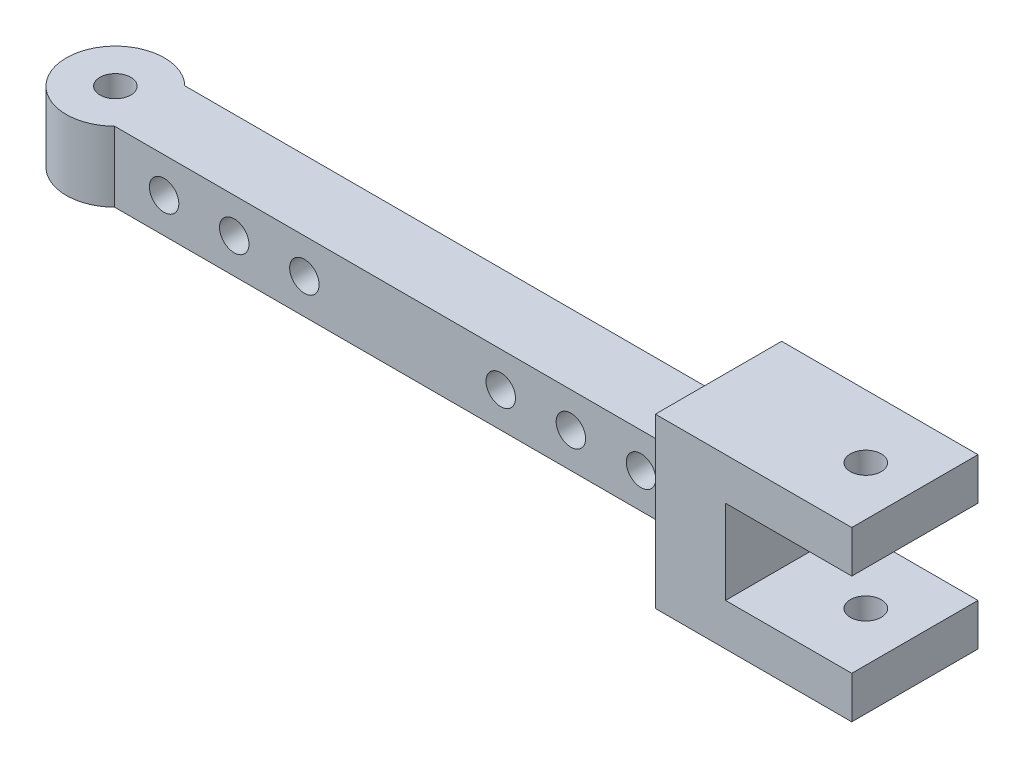
SolidWorks part; units mm, degrees
ref_plane "Front Plane" through (0, 0, 0) normal (0, 0, 1) x (1, 0, 0)
ref_plane "Top Plane" through (0, 0, 0) normal (0, 1, 0) x (1, 0, 0)
ref_plane "Right Plane" through (0, 0, 0) normal (1, 0, 0) x (0, 0, -1)
sketch "Sketch1" plane through (0, 0, 0) normal (0, 1, 0) x (1, 0, 0)
  line L1 (-25, 2.5) -> (25, 2.5)
  line L2 (-25, 2.5) -> (-25, -2.5)
  line L3 (-25, -2.5) -> (25, -2.5)
  line L4 (25, 2.5) -> (25, -2.5)
  line L5 (-25, 2.5) -> (25, -2.5) construction
  line L6 (-25, -2.5) -> (25, 2.5) construction
  point P0 (0, 0)
  dimension "D1" = 5
  dimension "D2" = 50
extrude "Boss-Extrude1" add sketch "Sketch1" along normal blind 5
sketch "Sketch7" plane through (0, 5, 0) normal (0, 1, 0) x (1, 0, 0)
  line L0 (25, -2.5) -> (25, 2.5) construction
  line L1 (18, 4.5) -> (32, 4.5)
  line L2 (18, 4.5) -> (18, -4.5)
  line L3 (18, -4.5) -> (32, -4.5)
  line L4 (32, 4.5) -> (32, -4.5)
  line L5 (18, 4.5) -> (32, -4.5) construction
  line L6 (18, -4.5) -> (32, 4.5) construction
  point P0 (25, 0)
  dimension "D1" = 9
  dimension "D2" = 14
extrude "Boss-Extrude4" add sketch "Sketch7" against normal blind 12 from offset 3.5
sketch "Sketch8" plane through (0, 5, 0) normal (0, 1, 0) x (1, 0, 0)
  line L0 (18, 2.5) -> (25, 2.5) construction
  line L1 (25, 2.5) -> (25, -2.5) construction
  line L2 (25, -2.5) -> (18, -2.5) construction
sketch "Sketch9" plane through (0, 8.5, 0) normal (0, 1, 0) x (1, 0, 0)
  line L0 (18, -4.5) -> (32, -4.5) construction
  line L1 (32, 4.5) -> (23, 4.5)
  line L2 (32, 4.5) -> (32, -4.5)
  line L3 (32, -4.5) -> (23, -4.5)
  line L4 (23, 4.5) -> (23, -4.5)
  dimension "D1" = 9
extrude "Cut-Extrude5" cut sketch "Sketch9" against normal blind 6 from offset 3 offset against normal yes
sketch "Sketch10" plane through (0, 8.5, 0) normal (0, 1, 0) x (1, 0, 0)
  line L0 (23, 4.5) -> (23, -4.5) construction
  line L1 (32, 4.5) -> (18, 4.5) construction
  line L2 (18, -4.5) -> (32, -4.5) construction
  line L3 (32, -4.5) -> (32, 4.5) construction
  dimension "D1" = 9
sketch "Sketch11" plane through (0, 8.5, 0) normal (0, 1, 0) x (1, 0, 0)
  line L0 (32, -4.5) -> (32, 4.5) construction
  circle A0 centre (28.5, 0) radius 1.1
  dimension "D1" = 3.5
  dimension "D2" = 2.2
extrude "Cut-Extrude6" cut sketch "Sketch11" against normal blind 12
sketch "Sketch15" plane through (0, 5, 0) normal (0, 1, 0) x (1, 0, 0)
  line L0 (-25, 2.5) -> (-25, -2.5) construction
  circle A0 centre (-25, 0) radius 1.1
sketch "Sketch16" plane through (0, 5, 0) normal (0, 1, 0) x (1, 0, 0)
  circle A0 centre (-25, 0) radius 3.5
extrude "Boss-Extrude7" add sketch "Sketch16" against normal blind 5 contours A0
extrude "Cut-Extrude9" cut sketch "Sketch15" against normal blind 5
sketch "Sketch18" plane through (0, 0, 2.5) normal (0, 0, 1) x (1, 0, 0)
  line L0 (-25.5253, 5) -> (-25.5253, 0) construction
  line L1 (-22.5505, 5) -> (-28.5, 5) construction
  line L2 (-28.5, 0) -> (-22.5505, 0) construction
  line L3 (28.5, 8.5) -> (28.5, -3.5) construction
  line L4 (18, 8.5) -> (32, 8.5) construction
  line L5 (18, -3.5) -> (32, -3.5) construction
  line L6 (32, 5.5) -> (32, 8.5) construction
  circle A0 centre (-14.0253, 2.5) radius 1.05
  circle A1 centre (9.9747, 2.5) radius 1.05
  circle A2 centre (-19.0253, 2.5) radius 1.05
  circle A3 centre (-9.0253, 2.5) radius 1.05
  circle A4 centre (4.9747, 2.5) radius 1.05
  circle A5 centre (14.9747, 2.5) radius 1.05
  dimension "D1" = 24
  dimension "D2" = 11.5
  dimension "D4" = 5
  dimension "D5" = 5
  dimension "D6" = 5
  dimension "D7" = 5
  dimension "D3" = 3.5
extrude "Cut-Extrude10" cut sketch "Sketch18" against normal blind 5
